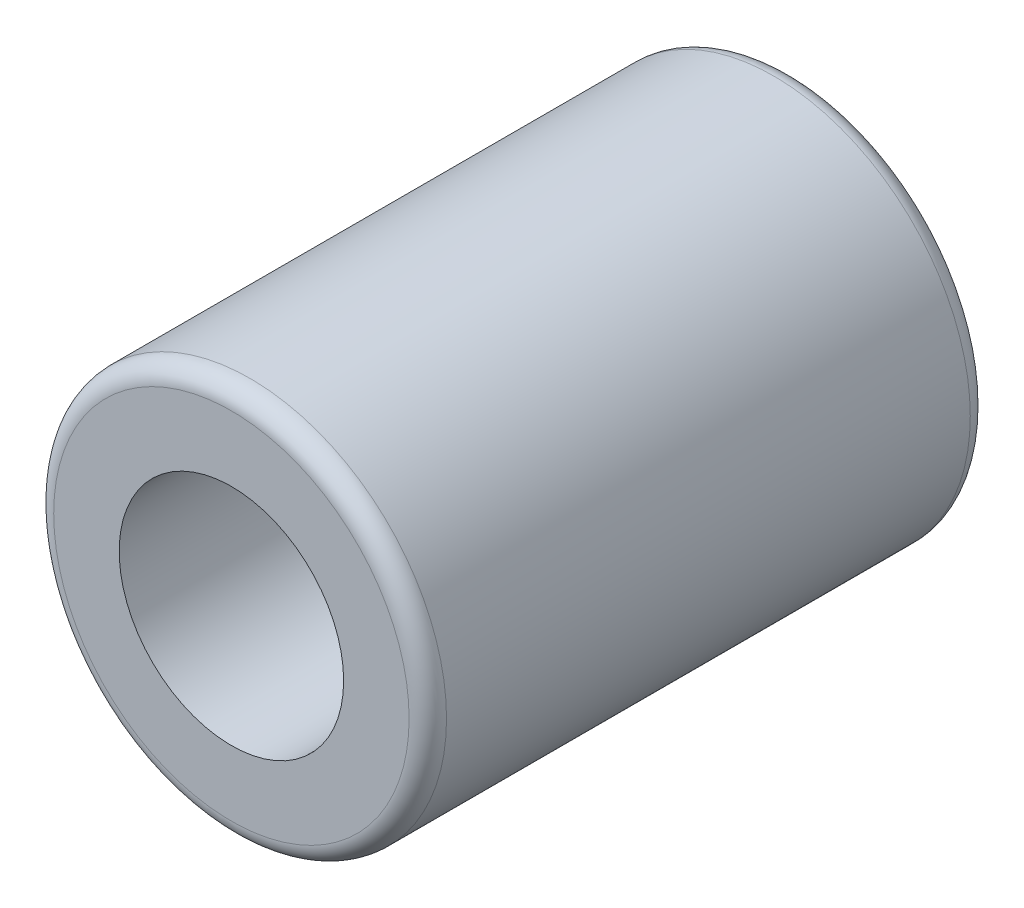
SolidWorks part; units mm, degrees
ref_plane "Plano frontal" through (0, 0, 0) normal (0, 0, 1) x (1, 0, 0)
ref_plane "Plano superior" through (0, 0, 0) normal (0, 1, 0) x (1, 0, 0)
ref_plane "Plano direito" through (0, 0, 0) normal (1, 0, 0) x (0, 0, -1)
sketch "Esboço1" plane through (0, 0, 0) normal (0, 0, 1) x (1, 0, 0)
  circle A0 centre (0, 0) radius 6
  circle A1 centre (0, 0) radius 10.5
  dimension "D1" = 12
  dimension "D2" = 21
extrude "Ressalto-extrusão1" add sketch "Esboço1" along normal blind 30
fillet "Filete1" radius 1 2 edges at (10.5, 0, 30) (10.5, 0, 0)
